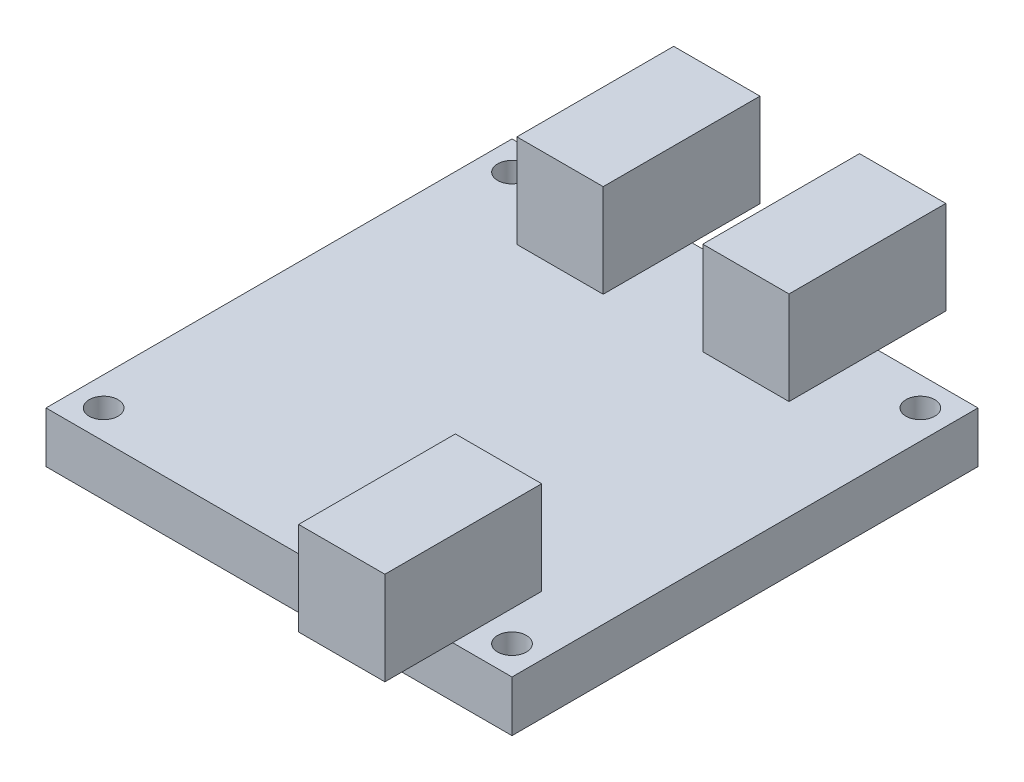
SolidWorks part; units mm, degrees
ref_plane "Front Plane" through (0, 0, 0) normal (0, 0, 1) x (1, 0, 0)
ref_plane "Top Plane" through (0, 0, 0) normal (0, 1, 0) x (1, 0, 0)
ref_plane "Right Plane" through (0, 0, 0) normal (1, 0, 0) x (0, 0, -1)
sketch "Sketch1" plane through (0, 0, 0) normal (0, 1, 0) x (1, 0, 0)
  line L1 (-27.495, -27.495) -> (27.495, -27.495)
  line L2 (-27.495, -27.495) -> (-27.495, 27.495)
  line L3 (-27.495, 27.495) -> (27.495, 27.495)
  line L4 (27.495, -27.495) -> (27.495, 27.495)
  line L5 (-27.495, -27.495) -> (27.495, 27.495) construction
  line L6 (-27.495, 27.495) -> (27.495, -27.495) construction
  point P0 (0, 0)
  dimension "D1" = 54.99
extrude "Boss-Extrude1" add sketch "Sketch1" along normal blind 6
sketch "Sketch5" plane through (0, 6, 0) normal (0, 1, 0) x (1, 0, 0)
  line L0 (-27.495, 27.495) -> (-27.495, -27.495) construction
  line L1 (27.495, -27.495) -> (27.495, 27.495) construction
  line L2 (27.495, 27.495) -> (-27.495, 27.495) construction
  line L3 (-27.495, -27.495) -> (27.495, -27.495) construction
  point P0 (-24.095, 24.095)
  point P1 (24.095, 24.095)
  point P2 (24.095, -24.095)
  point P3 (-24.095, -24.095)
  dimension "D1" = 3.4
  dimension "D2" = 3.4
  dimension "D3" = 3.4
  dimension "D4" = 3.4
  dimension "D5" = 3.4
  dimension "D6" = 3.4
  dimension "D7" = 3.4
  dimension "D8" = 3.4
hole_wizard "M3 Clearance Hole2" positions "Sketch6" profile "Sketch7" hole size "M3" standard "ANSI Metric" end condition through all
sketch "Sketch6" plane through (0, 6, 0) normal (0, 1, 0) x (1, 0, 0)
  point P0 (-24.095, 24.095)
  point P3 (24.095, 24.095)
  point P6 (24.095, -24.095)
  point P9 (-24.095, -24.095)
sketch "Sketch7" plane through (-24.095, 6, -24.095) normal (1, 0, 0) x (0, 0, 1)
  line L0 (0, 0) -> (0, 6)
  line L1 (0, 6) -> (1.7, 6)
  line L2 (1.7, 6) -> (1.7, 0)
  line L5 (1.7, 0) -> (0, 0)
  line L11 (0, -6.35) -> (0, 107.95) construction
  dimension "Thru Hole Dia." = 3.4
  dimension "Thru Hole Depth" = 6
sketch "Sketch8" plane through (0, 6, 0) normal (0, 1, 0) x (1, 0, 0)
  line L0 (27.495, 27.495) -> (-27.495, 27.495) construction
  line L1 (-16.415, 35.495) -> (-6.235, 35.495)
  line L2 (-16.415, 35.495) -> (-16.415, 16.995)
  line L3 (-16.415, 16.995) -> (-6.235, 16.995)
  line L4 (-6.235, 35.495) -> (-6.235, 16.995)
  line L5 (5.515, 35.495) -> (15.695, 35.495)
  line L6 (5.515, 35.495) -> (5.515, 16.995)
  line L7 (5.515, 16.995) -> (15.695, 16.995)
  line L8 (15.695, 35.495) -> (15.695, 16.995)
  line L9 (10.315, -16.995) -> (20.495, -16.995)
  line L10 (10.315, -16.995) -> (10.315, -35.495)
  line L11 (10.315, -35.495) -> (20.495, -35.495)
  line L12 (20.495, -16.995) -> (20.495, -35.495)
  line L13 (-27.495, -27.495) -> (27.495, -27.495) construction
  line L14 (27.495, -27.495) -> (27.495, 27.495) construction
  dimension "D1" = 10.18
  dimension "D2" = 10.18
  dimension "D3" = 10.18
  dimension "D4" = 18.5
  dimension "D5" = 18.5
  dimension "D6" = 18.5
  dimension "D7" = 8
  dimension "D8" = 8
  dimension "D9" = 8
  dimension "D10" = 11.8
  dimension "D11" = 11.75
  dimension "D12" = 7
extrude "Boss-Extrude2" add sketch "Sketch8" along normal blind 11
